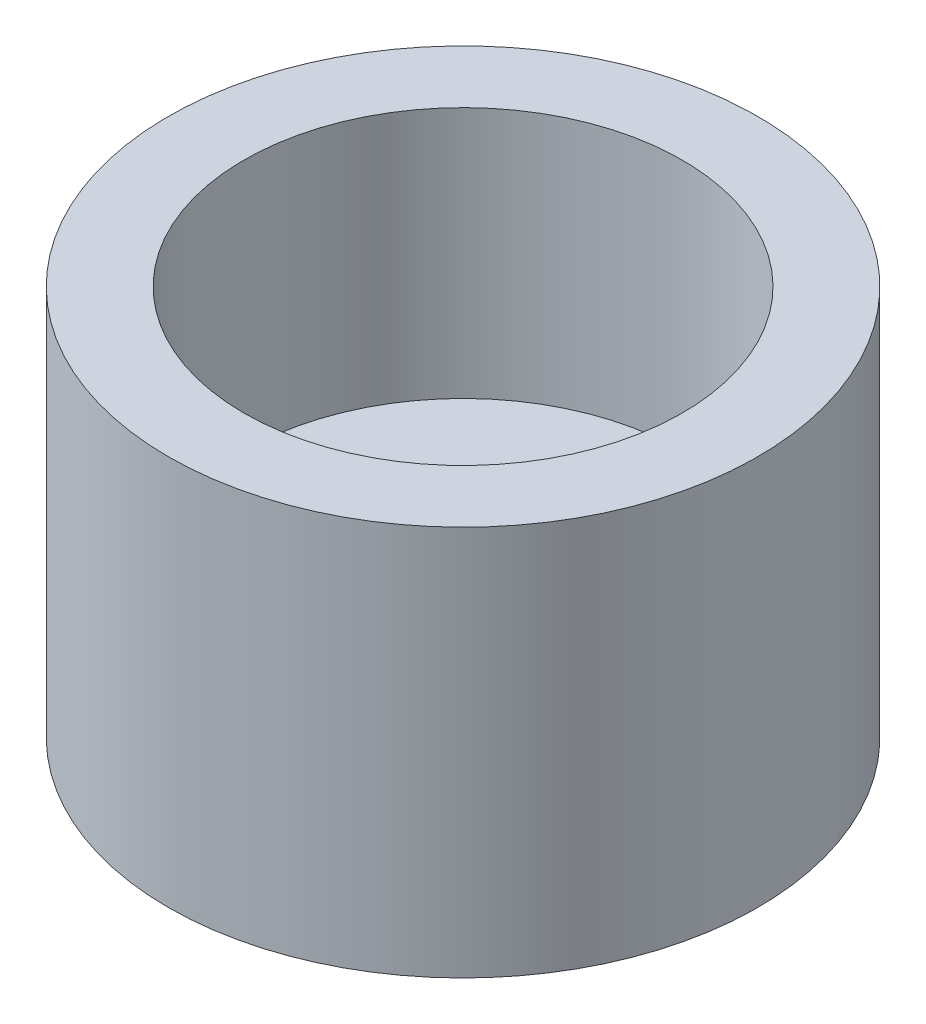
SolidWorks part; units mm, degrees
ref_plane "Front Plane" through (0, 0, 0) normal (0, 0, 1) x (1, 0, 0)
ref_plane "Top Plane" through (0, 0, 0) normal (0, 1, 0) x (1, 0, 0)
ref_plane "Right Plane" through (0, 0, 0) normal (1, 0, 0) x (0, 0, -1)
sketch "Sketch1" plane through (0, 0, 0) normal (0, 0, 1) x (1, 0, 0)
  line L0 (0, 989.371) -> (0, -862.371) construction
  line L1 (274.4839, 14.3387) -> (274.4839, -239.6613)
  line L2 (274.4839, -239.6613) -> (909.4839, -239.6613)
  line L3 (909.4839, -239.6613) -> (909.4839, -493.6613)
  line L4 (909.4839, -493.6613) -> (1163.4839, -493.6613)
  line L5 (1163.4839, -493.6613) -> (1163.4839, 1030.3387)
  line L6 (1163.4839, 1030.3387) -> (909.4839, 1030.3387)
  line L7 (909.4839, 1030.3387) -> (909.4839, 14.3387)
  line L8 (909.4839, 14.3387) -> (274.4839, 14.3387)
  dimension "D1" = 1524
  dimension "D2" = 254
  dimension "D3" = 635
  dimension "D4" = 254
  dimension "D5" = 1016
revolve "Revolve-Thin1" add sketch "Sketch1" angle 360 about L0
